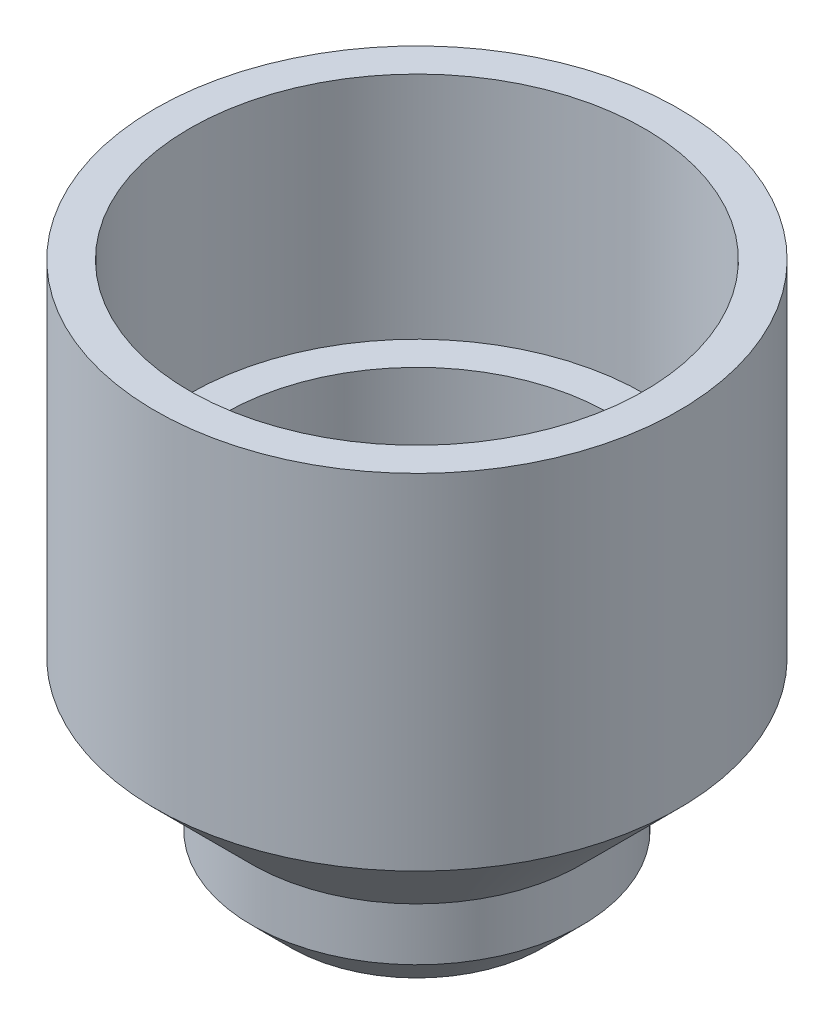
SolidWorks part; units mm, degrees
ref_plane "Płaszczyzna przednia" through (0, 0, 0) normal (0, 0, 1) x (1, 0, 0)
ref_plane "Płaszczyzna górna" through (0, 0, 0) normal (0, 1, 0) x (1, 0, 0)
ref_plane "Płaszczyzna prawa" through (0, 0, 0) normal (1, 0, 0) x (0, 0, -1)
sketch "Sketch1" plane through (0, 0, 0) normal (0, 0, 1) x (1, 0, 0)
  line L0 (-11.4, 0) -> (11.4, 0) construction
  line L1 (-7.4, -4) -> (7.4, -4) construction
  line L2 (-11.4, 0) -> (-7.4, -4) construction
  line L3 (11.4, 0) -> (7.4, -4) construction
  line L4 (0, 51.2742) -> (0, -55.0085) construction
  line L6 (7.4, -4) -> (11.4, 0)
  line L7 (7.4, -1) -> (11.4, 3)
  line L8 (7.4, -1) -> (7.4, -4)
  line L12 (11.4, 0) -> (11.4, 15)
  line L13 (8.4, 15) -> (8.4, 0)
  line L14 (8.4, 15) -> (11.4, 15)
  line L15 (-29.798, -4) -> (34.28, -4) construction
  line L16 (8.4, 5) -> (9.9, 5)
  line L17 (9.9, 15) -> (9.9, 5)
  line L30 (7.4, -4) -> (5.4803, -5.9197)
  line L31 (7.4, -1) -> (5.4803, -2.9197)
  line L32 (5.4803, -2.9197) -> (5.4803, -5.9197)
  line L33 (5.4803, -5.9197) -> (5.4803, -8.2153)
  line L34 (5.4803, -8.2153) -> (7.1803, -6.5153)
  line L35 (7.1803, -4.2197) -> (7.1803, -6.5153)
  point P3 (0, 0)
  dimension "D1" = 22.8
  dimension "D2" = 14.8
  dimension "D3" = 4
  dimension "D4" = 15
  dimension "D5" = 3
  dimension "D6" = 3
  dimension "D7" = 1.5
  dimension "D9" = 1.7
  dimension "D8" = 10
revolve "Revolve1" add sketch "Sketch1" angle 360 about L4
